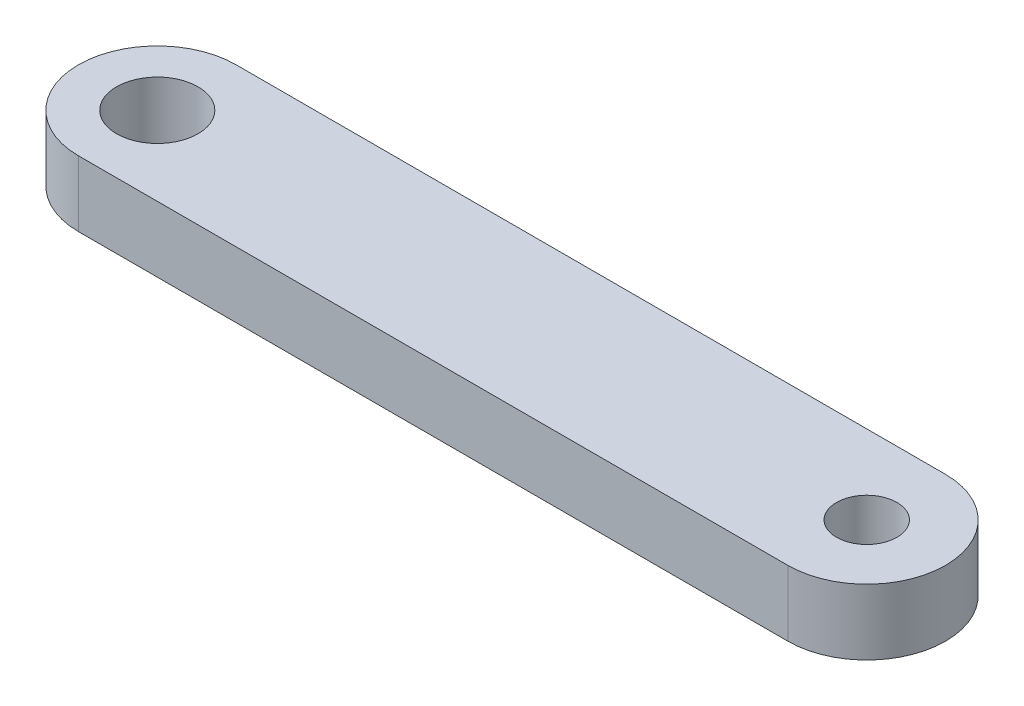
SolidWorks part; units mm, degrees
ref_plane "Front Plane" through (0, 0, 0) normal (0, 0, 1) x (1, 0, 0)
ref_plane "Top Plane" through (0, 0, 0) normal (0, 1, 0) x (1, 0, 0)
ref_plane "Right Plane" through (0, 0, 0) normal (1, 0, 0) x (0, 0, -1)
other "Configuration Table"
sketch "草图1" plane through (0, 0, 0) normal (0, 1, 0) x (1, 0, 0)
  line L0 (-13.5, 0) -> (13.5, 0) construction
  line L1 (-13.5, 3) -> (13.5, 3)
  line L2 (-13.5, -3) -> (13.5, -3)
  arc A0 (-13.5, 3) -> (-13.5, -3) centre (-13.5, 0) ccw
  arc A1 (13.5, -3) -> (13.5, 3) centre (13.5, 0) ccw
  circle A2 centre (-13.5, 0) radius 1.55
  circle A3 centre (13.5, 0) radius 1.15
  point P2 (0, 0)
  dimension "D3" = 3.1
  dimension "D4" = 2.3
  dimension "D1" = 27
  dimension "D2" = 6
extrude "凸台-拉伸1" add sketch "草图1" along normal blind 2.5
sketch "草图2" plane through (0, 2.5, 0) normal (0, 1, 0) x (1, 0, 0)
  line L0 (-9.5, 3) -> (-9.5, -3) construction
  line L1 (13.5, 3) -> (-13.5, 3) construction
  line L2 (-13.5, -3) -> (13.5, -3) construction
  arc A0 (-13.5, 3) -> (-13.5, -3) centre (-13.5, 0) ccw construction
  dimension "D1" = 4
